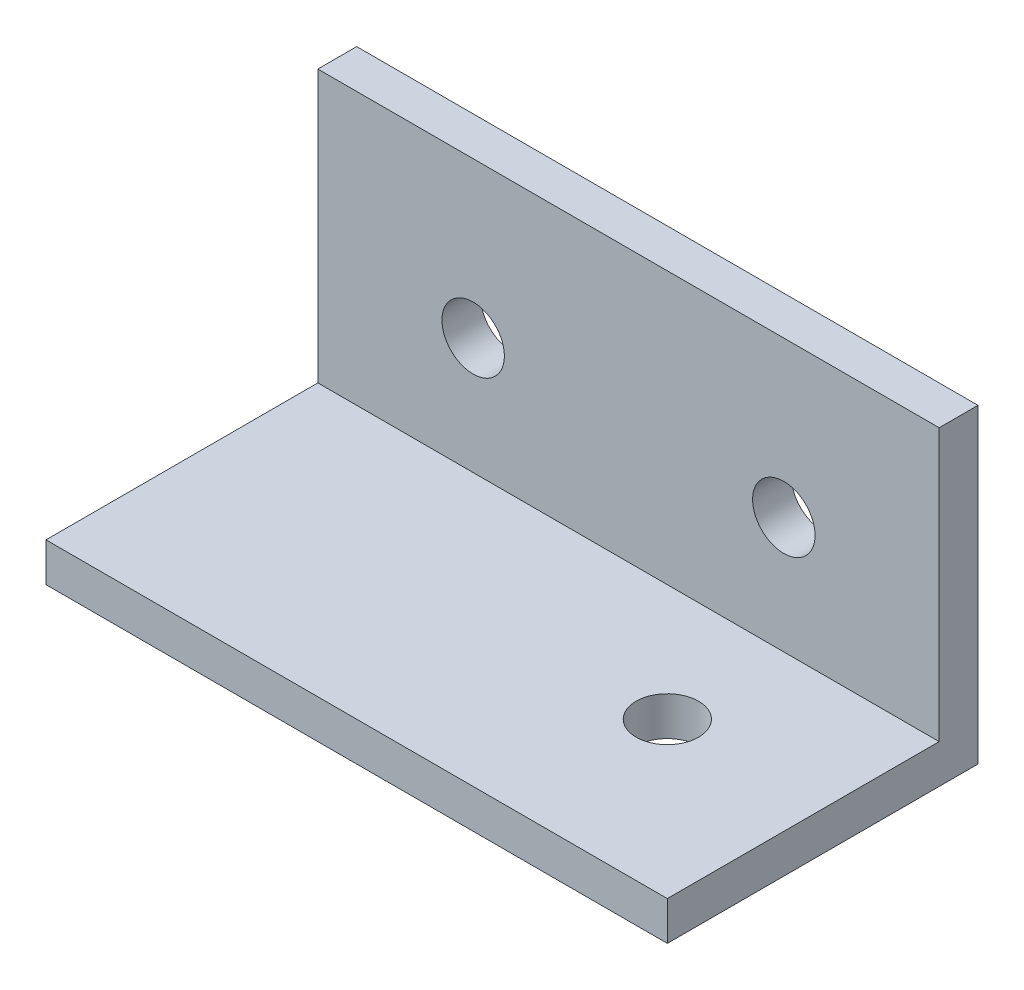
SolidWorks part; units mm, degrees
ref_plane "Front Plane" through (0, 0, 0) normal (0, 0, 1) x (1, 0, 0)
ref_plane "Top Plane" through (0, 0, 0) normal (0, 1, 0) x (1, 0, 0)
ref_plane "Right Plane" through (0, 0, 0) normal (1, 0, 0) x (0, 0, -1)
ref_plane "Plane1" through (0, 63.5, 0) normal (0, 1, 0) x (1, 0, 0)
sketch "Sketch1" plane through (0, 63.5, 0) normal (0, 1, 0) x (1, 0, 0)
  line L0 (0, 0) -> (0, -25.4)
  line L1 (0, -25.4) -> (50.8, -25.4)
  line L2 (50.8, -25.4) -> (50.8, 0)
  line L3 (50.8, 0) -> (0, 0)
extrude "Boss-Extrude1" add sketch "Sketch1" against normal blind 25.4
sketch "Sketch2" plane through (50.8, 0, 0) normal (1, 0, 0) x (0, 0, -1)
  line L0 (-25.4, 63.5) -> (-25.4, 41.275)
  line L1 (-25.4, 41.275) -> (-3.175, 41.275)
  line L2 (-3.175, 41.275) -> (-3.175, 63.5)
  line L3 (-3.175, 63.5) -> (-25.4, 63.5)
extrude "Cut-Extrude1" cut sketch "Sketch2" against normal through all
hole_wizard "#7 (0.201) Diameter Hole1" positions "Sketch4" profile "Sketch3" hole size "#7" standard "ANSI Inch"
sketch "Sketch4" plane through (0, 38.1, 0) normal (0, -1, 0) x (1, 0, 0)
  point P0 (-12.7, -12.7)
  point P1 (38.1, 12.7)
sketch "Sketch3" plane through (-12.7, 38.1, -12.7) normal (1, 0, 0) x (0, 0, -1)
  line L0 (0, 0) -> (0, 25.4)
  line L1 (0, 25.4) -> (2.5527, 25.4)
  line L2 (2.5527, 25.4) -> (2.5527, 0)
  line L5 (2.5527, 0) -> (0, 0)
  line L11 (0, -6.35) -> (0, 107.95) construction
  dimension "Thru Hole Dia." = 5.1054
  dimension "Thru Hole Depth" = 25.4
hole_wizard "#7 (0.201) Diameter Hole2" positions "Sketch6" profile "Sketch5" hole size "#7" standard "ANSI Inch"
sketch "Sketch6" plane through (0, 0, 3.175) normal (0, 0, 1) x (1, 0, 0)
  point P0 (38.1, 50.8)
  point P1 (12.7, 50.8)
sketch "Sketch5" plane through (38.1, 50.8, 3.175) normal (1, 0, 0) x (0, -1, 0)
  line L0 (0, 0) -> (0, 3.175)
  line L1 (0, 3.175) -> (2.5527, 3.175)
  line L2 (2.5527, 3.175) -> (2.5527, 0)
  line L5 (2.5527, 0) -> (0, 0)
  line L11 (0, -6.35) -> (0, 107.95) construction
  dimension "Thru Hole Dia." = 5.1054
  dimension "Thru Hole Depth" = 3.175
